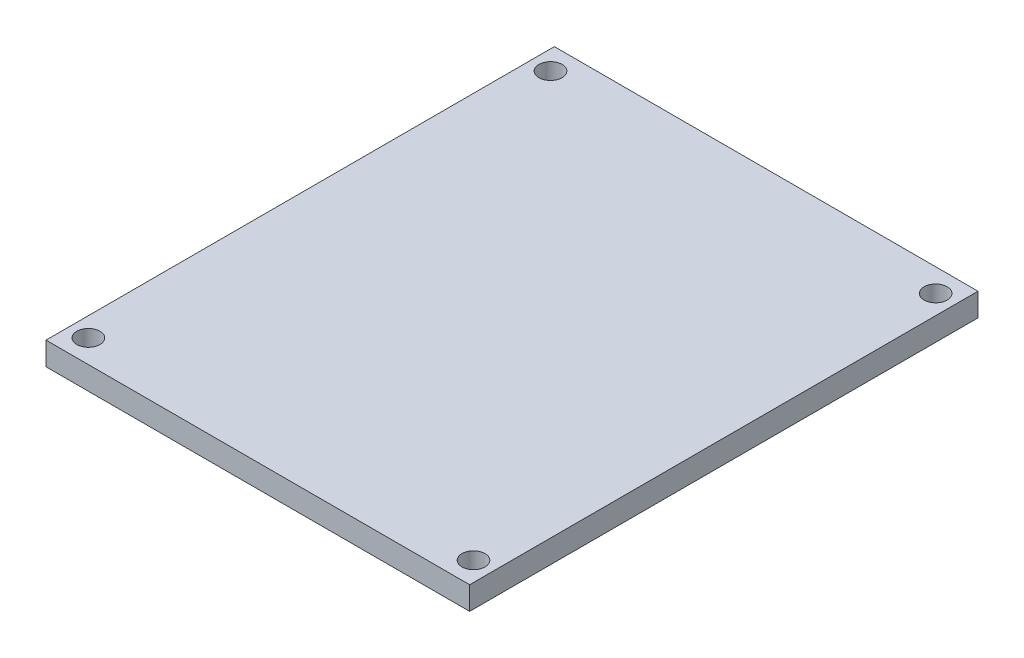
SolidWorks part; units mm, degrees
ref_plane "Plan de face" through (0, 0, 0) normal (0, 0, 1) x (1, 0, 0)
ref_plane "Plan de dessus" through (0, 0, 0) normal (0, 1, 0) x (1, 0, 0)
ref_plane "Plan de droite" through (0, 0, 0) normal (1, 0, 0) x (0, 0, -1)
sketch "Esquisse1" plane through (0, 0, 0) normal (0, 1, 0) x (1, 0, 0)
  line L1 (-27.5, -33) -> (27.5, -33)
  line L2 (-27.5, -33) -> (-27.5, 33)
  line L3 (-27.5, 33) -> (27.5, 33)
  line L4 (27.5, -33) -> (27.5, 33)
  line L5 (-27.5, -33) -> (27.5, 33) construction
  line L6 (-27.5, 33) -> (27.5, -33) construction
  line L11 (-25, -30) -> (25, 30) construction
  line L12 (-25, 30) -> (25, -30) construction
  circle A0 centre (-25, 30) radius 1.5
  circle A1 centre (25, 30) radius 1.5
  circle A2 centre (25, -30) radius 1.5
  circle A3 centre (-25, -30) radius 1.5
  point P0 (0, 0)
  point P6 (0, 0)
  dimension "D1" = 60
  dimension "D2" = 50
  dimension "D3" = 55
extrude "Boss.-Extru.1" add sketch "Esquisse1" along normal blind 3
